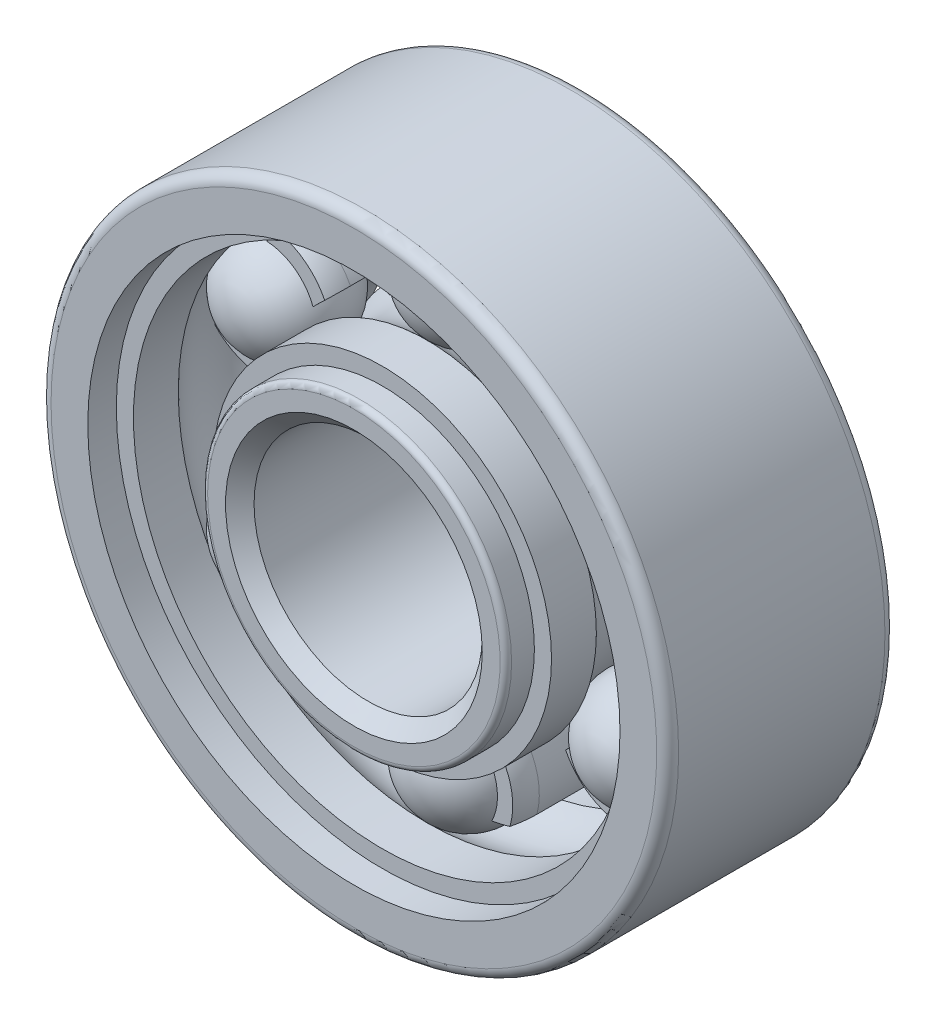
SolidWorks part; units mm, degrees
ref_plane "Front Plane" through (0, 0, 0) normal (0, 0, 1) x (1, 0, 0)
ref_plane "Top Plane" through (0, 0, 0) normal (0, 1, 0) x (1, 0, 0)
ref_plane "Right Plane" through (0, 0, 0) normal (1, 0, 0) x (0, 0, -1)
sketch "Sketch1" plane through (0, 0, 0) normal (1, 0, 0) x (0, 0, -1)
  line L0 (-3.175, 0) -> (3.175, 0) construction
  line L9 (0, 8.7312) -> (0, 0) construction
  line L10 (-3.175, 3.175) -> (3.175, 3.175)
  line L11 (3.175, 3.175) -> (3.175, 4.7053)
  line L12 (3.175, 4.7053) -> (-3.175, 4.7053)
  line L13 (-3.175, 4.7053) -> (-3.175, 3.175)
  line L14 (-3.175, 6.9279) -> (3.175, 6.9279)
  line L15 (3.175, 6.9279) -> (3.175, 8.7312)
  line L16 (3.175, 8.7312) -> (-3.175, 8.7312)
  line L17 (-3.175, 8.7312) -> (-3.175, 6.9279)
  line L18 (-1.5875, 5.8166) -> (1.5875, 5.8166) construction
  line L20 (-3.175, 4.2291) -> (3.175, 4.2291) construction
  line L22 (-1.5875, 5.8166) -> (-2.3812, 5.8166)
  line L23 (-2.3812, 5.8166) -> (-3.175, 5.8166)
  line L24 (-3.175, 7.4041) -> (3.175, 7.4041) construction
  line L25 (-3.175, 6.9279) -> (-3.175, 4.7053) construction
  line L26 (-2.3812, 7.4041) -> (-2.3812, 4.2291) construction
  line L29 (-0.635, 7.4041) -> (-0.635, 4.2291) construction
  line L30 (1.9844, 7.4041) -> (1.9844, 4.2291) construction
  line L31 (-0.635, 6.6104) -> (1.9844, 6.6104)
  line L32 (-0.635, 5.0229) -> (1.9844, 5.0229)
  line L33 (-0.635, 6.6104) -> (-0.635, 5.0229)
  line L34 (1.9844, 6.6104) -> (1.9844, 5.0229)
  circle A0 centre (0, 5.8166) radius 1.5875
  circle A1 centre (0, 5.8166) radius 1.9844 construction
  arc A2 (-3.175, 8.4264) -> (-2.8702, 8.7312) centre (-2.8702, 8.4264) cw
  point P17 (0, 7.4041)
  point P27 (0, 4.2291)
  dimension "OD" = 17.4625
  dimension "ID" = 6.35
  dimension "Ball Diameter" = 3.175
  dimension "D2" = 3.9688
  dimension "Radius" = 0.3048
  dimension "Ball Pattern Diameter" = 11.6332
  dimension "D6" = 2.2225
  dimension "Width" = 6.35
  dimension "D1" = 1.5875
  dimension "D3" = 2.2225
sketch "Sketch2" plane through (0, 0, 0) normal (0, 0, 1) x (1, 0, 0)
  circle A0 centre (0, 0) radius 5.8166 construction
  circle A1 centre (0, 5.8166) radius 1.5875
  circle A2 centre (5.0373, 2.9083) radius 1.5875
  circle A3 centre (5.0373, -2.9083) radius 1.5875
  circle A4 centre (0, -5.8166) radius 1.5875
  circle A5 centre (-5.0373, -2.9083) radius 1.5875
  circle A6 centre (-5.0373, 2.9083) radius 1.5875
  circle A11 centre (0, 0) radius 3.175 construction
  circle A12 centre (0, 0) radius 8.7312 construction
  point P36 (0, 0)
  dimension "OD" = 17.4625
  dimension "ID" = 6.35
  dimension "No. of Balls" = 6
sketch "Sketch3" plane through (0, 0, 0) normal (1, 0, 0) x (0, 0, -1)
  line L1 (3.175, 3.175) -> (3.175, 4.7053) construction
  line L2 (-3.175, 4.7053) -> (-3.175, 3.175) construction
  line L3 (3.175, 4.7053) -> (-3.175, 4.7053) construction
  line L5 (3.175, 3.175) -> (3.175, 4.7053)
  line L6 (-3.175, 4.7053) -> (-3.175, 3.175)
  line L7 (3.175, 4.7053) -> (-3.175, 4.7053)
  line L8 (-3.175, 8.7312) -> (-3.175, 6.9279) construction
  line L9 (3.175, 8.7312) -> (-3.175, 8.7312) construction
  line L10 (3.175, 6.9279) -> (3.175, 8.7312) construction
  line L11 (-3.175, 6.9279) -> (3.175, 6.9279) construction
  line L12 (-3.175, 8.7312) -> (-3.175, 6.9279)
  line L13 (3.175, 8.7312) -> (-3.175, 8.7312)
  line L14 (3.175, 6.9279) -> (3.175, 8.7312)
  line L15 (-3.175, 6.9279) -> (3.175, 6.9279)
  line L16 (-3.175, 3.175) -> (3.175, 3.175) construction
  line L17 (-3.175, 3.175) -> (3.175, 3.175)
revolve "Revolve2" add sketch "Sketch3" angle 360 about L0
sketch "Sketch4" plane through (0, 0, 0) normal (1, 0, 0) x (0, 0, -1)
  circle A0 centre (0, 5.8166) radius 1.5875 construction
  circle A1 centre (0, 5.8166) radius 1.5875
revolve "Cut-Revolve1" cut sketch "Sketch4" angle 360 about L0
sketch "Sketch6" plane through (0, 0, 0) normal (1, 0, 0) x (0, 0, -1)
  line L0 (0, 8.7312) -> (0, 0) construction
  line L1 (-3.175, 7.4041) -> (-2.3812, 7.4041)
  line L2 (-3.175, 7.4041) -> (-3.175, 4.2291)
  line L3 (-3.175, 4.2291) -> (-2.3812, 4.2291)
  line L4 (-2.3812, 7.4041) -> (-2.3812, 4.2291)
  line L5 (0, 8.7312) -> (0, 0) construction
  line L6 (2.3812, 7.4041) -> (2.3812, 4.2291)
  line L7 (3.175, 4.2291) -> (2.3812, 4.2291)
  line L8 (3.175, 7.4041) -> (3.175, 4.2291)
  line L9 (3.175, 7.4041) -> (2.3812, 7.4041)
revolve "Cut-Revolve2" cut sketch "Sketch6" angle 360 about L0
fillet "Fillet1" radius 0.3048 2 edges at (8.7312, 0, 3.175) (8.7312, 0, -3.175)
chamfer "Chamfer1" distance 0.3969 angle 45 2 edges at (3.175, 0, -3.175) (3.175, 0, 3.175)
fillet "Fillet2" radius 0.1588 2 edges at (4.2291, 0, -3.175) (4.2291, 0, 3.175)
sketch "Sketch5" plane through (0, 0, 0) normal (1, 0, 0) x (0, 0, -1)
  line L0 (-1.5875, 5.8166) -> (1.5875, 5.8166) construction
  line L1 (-1.5875, 5.8166) -> (1.5875, 5.8166)
  circle A0 centre (0, 5.8166) radius 1.5875 construction
  arc A1 (1.5875, 5.8166) -> (-1.5875, 5.8166) centre (0, 5.8166) ccw
revolve "Revolve3" add sketch "Sketch5" angle 360 about L18
pattern_circular "CirPattern1" count 6 over 360 about axis through (0, 0, 0) along (0, 0, 1) of bodies 109
sketch "Sketch9" plane through (0, 0, 0) normal (1, 0, 0) x (0, 0, -1)
  line L0 (-0.635, 5.0229) -> (1.9844, 5.0229) construction
  line L1 (1.9844, 6.6104) -> (1.5875, 6.6104)
  line L2 (1.9844, 6.6104) -> (1.9844, 5.0229)
  line L3 (1.9844, 5.0229) -> (1.5875, 5.0229)
  line L4 (1.5875, 6.6104) -> (1.5875, 5.0229)
revolve "Revolve4" add sketch "Sketch9" angle 360 about L0
sketch "Sketch7" plane through (0, 0, 0) normal (1, 0, 0) x (0, 0, -1)
  line L0 (1.9844, 6.6104) -> (1.9844, 5.0229) construction
  line L2 (-0.635, 7.4041) -> (-0.635, 4.2291) construction
  line L3 (-0.635, 7.6966) -> (-0.635, 7.2716)
  line L6 (0, 7.801) -> (1.9844, 7.801)
  line L7 (1.9844, 7.801) -> (1.9844, 5.8166)
  line L10 (0, 8.7312) -> (0, 0) construction
  line L13 (1.5875, 5.8166) -> (1.9844, 5.8166)
  circle A0 centre (0, 5.8166) radius 1.5875 construction
  arc A1 (1.5875, 5.8166) -> (-0.635, 7.2716) centre (0, 5.8166) ccw
  circle A4 centre (0, 5.8166) radius 1.9844 construction
  arc A5 (0, 7.801) -> (-0.635, 7.6966) centre (0, 5.8166) ccw
revolve "Revolve5" add sketch "Sketch7" angle 360 about L18
pattern_circular "CirPattern2" count 6 over 360 about axis through (0, 0, 0) along (0, 0, 1) of "Revolve5"
sketch "Sketch10" plane through (0, 0, 0) normal (0, 0, 1) x (1, 0, 0)
  circle A0 centre (0, 0) radius 5.0229
  circle A1 centre (0, 0) radius 6.6104
extrude "Cut-Extrude1" cut sketch "Sketch10" against normal through all both and the other way through all flip side to cut
equation "\"D1@CirPattern1\"=\"No. of Balls@Sketch2\""
equation "\"D6@Sketch1\"=\"Ball Diameter@Sketch1\"*0.7"
equation "\"D1@Fillet1\"=\"Radius@Sketch1\""
equation "\"D1@Chamfer1\"=\"Width@Sketch1\" / 16"
equation "\"D1@Sketch1\"=\"Ball Diameter@Sketch1\"*0.5"
equation "\"D1@CirPattern2\"=\"No. of Balls@Sketch2\""
equation "\"D2@Sketch1\"=\"Ball Diameter@Sketch1\"*1.25"
equation "\"D3@Sketch1\"=\"Ball Diameter@Sketch1\"*0.7"
equation "\"D1@Fillet2\"=\"Width@Sketch1\"/40"
equation "\"OD@Sketch2\" = \"OD@Sketch1\""
equation "\"ID@Sketch2\"=\"ID@Sketch1\""
